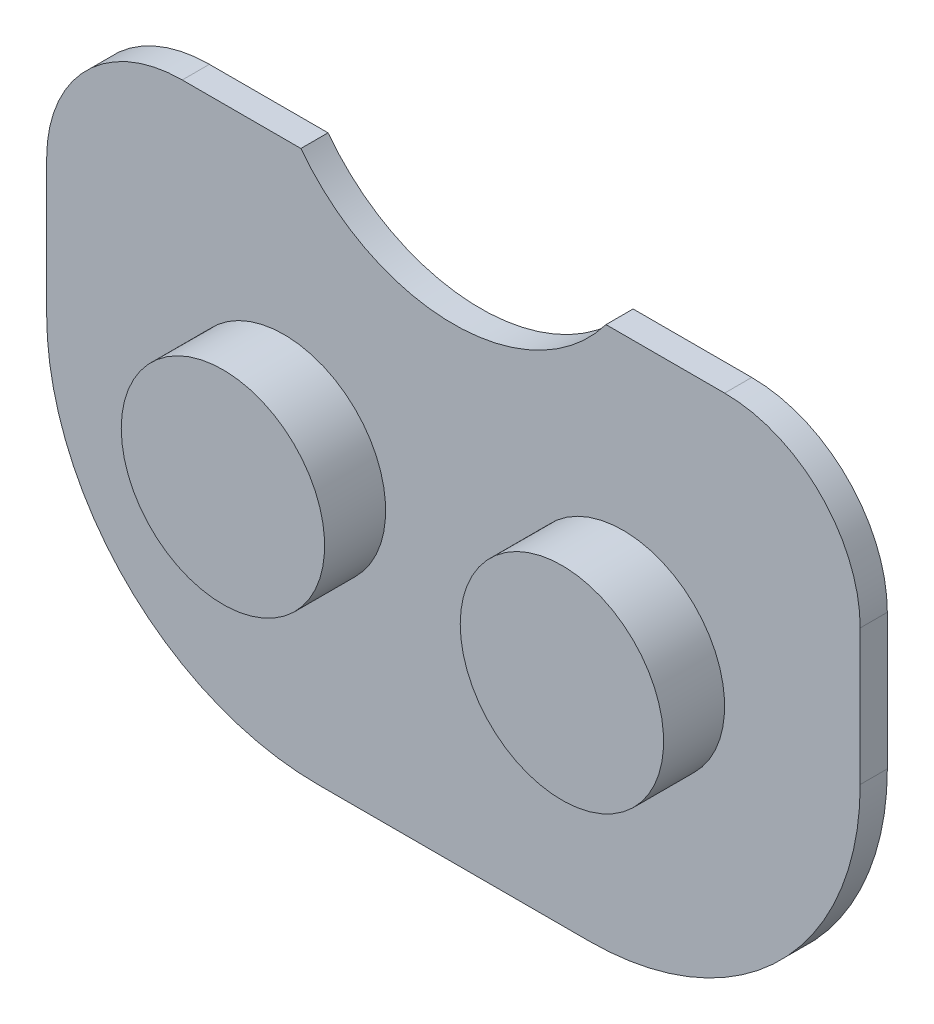
SolidWorks part; units mm, degrees
ref_plane "前视基准面" through (0, 0, 0) normal (0, 0, 1) x (1, 0, 0)
ref_plane "上视基准面" through (0, 0, 0) normal (0, 1, 0) x (1, 0, 0)
ref_plane "右视基准面" through (0, 0, 0) normal (1, 0, 0) x (0, 0, -1)
other "Configuration Table"
sketch "草图1" plane through (0, 0, 0) normal (0, 0, 1) x (1, 0, 0)
  line L1 (10, -20) -> (-10, -20)
  line L2 (30, 0) -> (30, 10)
  line L3 (20, 20) -> (-20, 20)
  line L4 (-30, 0) -> (-30, 10)
  line L5 (30, -20) -> (-30, 20) construction
  line L6 (30, 20) -> (-30, -20) construction
  arc A0 (-30, 10) -> (-20, 20) centre (-20, 10) cw
  arc A1 (30, 10) -> (20, 20) centre (20, 10) ccw
  circle A4 centre (0, 28.5) radius 14.1
  arc A5 (30, 0) -> (10, -20) centre (10, 0) cw
  arc A6 (-10, -20) -> (-30, 0) centre (-10, 0) cw
  point P0 (0, 0)
  dimension "D3" = 10
  dimension "D4" = 28.2
  dimension "D6" = 20
  dimension "D1" = 60
  dimension "D2" = 40
  dimension "D5" = 8.5
extrude "凸台-拉伸1" add sketch "草图1" along normal blind 2 contours A6 L1 A5 L2 A1 L3 A4 A0 L4
sketch "草图3" plane through (0, 0, 0) normal (0, 0, 1) x (1, 0, 0)
  line L0 (20, 20) -> (11.2499, 20) construction
  line L1 (0, 14.4) -> (0, -20) construction
  line L2 (10, -20) -> (-10, -20) construction
  circle A0 centre (-12.5, 0) radius 7.5
  circle A1 centre (12.5, 0) radius 7.5
  arc A2 (-11.2499, 20) -> (11.2499, 20) centre (0, 28.5) ccw construction
  dimension "D1" = 15
  dimension "D2" = 15
  dimension "D3" = 20
  dimension "D4" = 12.5
  dimension "D5" = 12.5
extrude "凸台-拉伸2" add sketch "草图3" along normal blind 6.5
